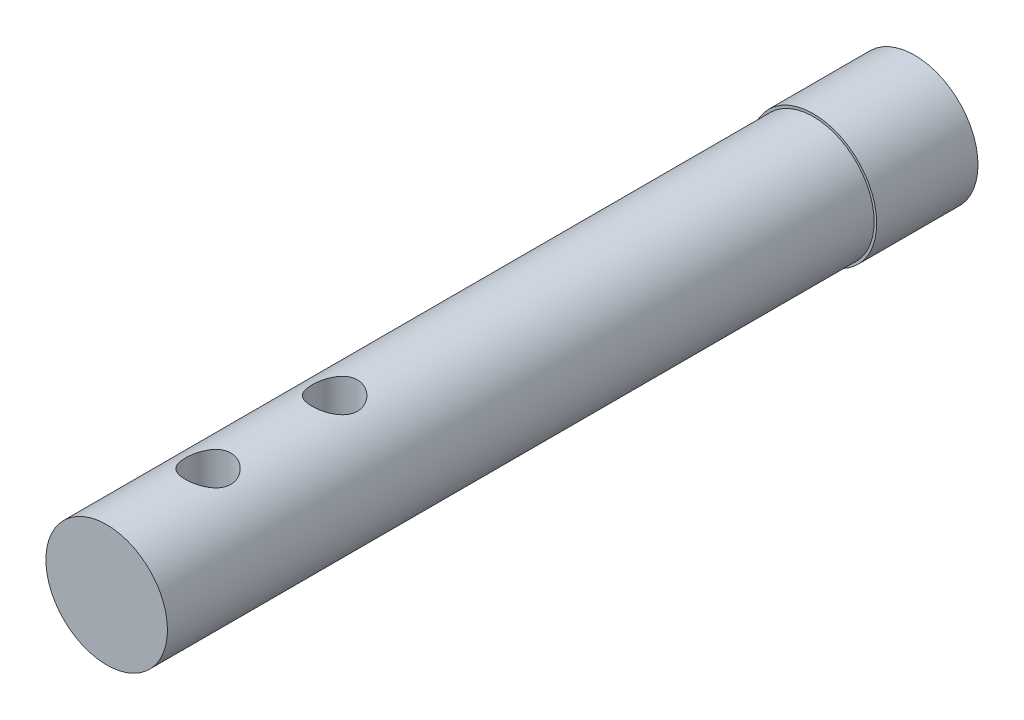
SolidWorks part; units mm, degrees
material "Galvanized Steel"
ref_plane "Front Plane" through (0, 0, 0) normal (0, 0, 1) x (1, 0, 0)
ref_plane "Top Plane" through (0, 0, 0) normal (0, 1, 0) x (1, 0, 0)
ref_plane "Right Plane" through (0, 0, 0) normal (1, 0, 0) x (0, 0, -1)
sketch "Sketch1" plane through (0, 0, 0) normal (0, 0, 1) x (1, 0, 0)
  circle A0 centre (0, 0) radius 10
  dimension "D1" = 20
extrude "Boss-Extrude1" add sketch "Sketch1" along normal blind 15
sketch "Sketch2" plane through (0, 0, 15) normal (0, 0, 1) x (1, 0, 0)
  circle A0 centre (0, 0) radius 12.5
  dimension "D1" = 25
extrude "Boss-Extrude2" add sketch "Sketch2" along normal blind 20
sketch "Sketch3" plane through (0, 0, 35) normal (0, 0, 1) x (1, 0, 0)
  circle A0 centre (0, 0) radius 12
  dimension "D1" = 24
extrude "Boss-Extrude3" add sketch "Sketch3" along normal blind 139.5
sketch "Sketch4" plane through (0, 0, 0) normal (0, 1, 0) x (1, 0, 0)
  line L0 (-12, -174.5) -> (12, -174.5) construction
  circle A0 centre (0, -154.5) radius 4.5
  dimension "D1" = 9
  dimension "D2" = 20
extrude "Cut-Extrude1" cut sketch "Sketch4" against normal through all both and the other way through all
sketch "Sketch5" plane through (0, 0, 0) normal (0, 1, 0) x (1, 0, 0)
  line L1 (12.5, -15) -> (-37.6297, -15)
  line L2 (12.5, -15) -> (12.5, 4.8742)
  line L3 (12.5, 4.8742) -> (-37.6297, 4.8742)
  line L4 (-37.6297, -15) -> (-37.6297, 4.8742)
extrude "Cut-Extrude2" cut sketch "Sketch5" against normal through all both and the other way through all
pattern_linear "LPattern1" count 2 spacing 25 along (0, 0, -1) of "Cut-Extrude1"
